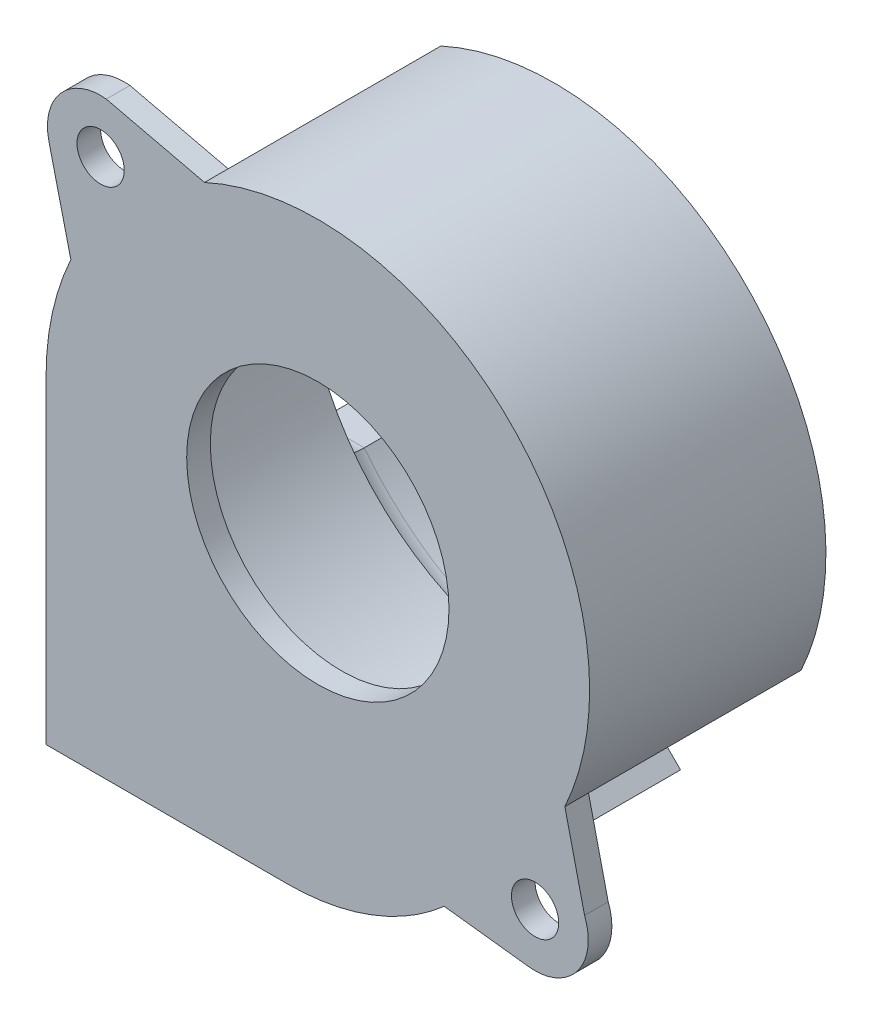
SolidWorks part; units mm, degrees
ref_plane "前视基准面" through (0, 0, 0) normal (0, 0, 1) x (1, 0, 0)
ref_plane "上视基准面" through (0, 0, 0) normal (0, 1, 0) x (1, 0, 0)
ref_plane "右视基准面" through (0, 0, 0) normal (1, 0, 0) x (0, 0, -1)
other "Configuration Table"
sketch "草图1" plane through (0, 0, 0) normal (0, 0, 1) x (1, 0, 0)
  line L4 (-23, 0) -> (-23, -27)
  line L5 (-23, -27) -> (-2.527, -27)
  arc A6 (15.3161, -17.1586) -> (13.0537, -19.5395) centre (28.6345, -32.079) ccw
  arc A7 (15.3161, -17.1586) -> (-23, 0) centre (0, 0) ccw
  arc A8 (-2.527, -27) -> (13.0537, -19.5395) centre (-2.527, -7) ccw
  circle A9 centre (0, 0) radius 11.1
  dimension "D1" = 22.2
extrude "凸台-拉伸1" add sketch "草图1" along normal blind 20
sketch "草图3" plane through (0, 0, 0) normal (0, 0, -1) x (-1, 0, 0)
  circle A0 centre (0, 0) radius 21.1
  dimension "D1" = 42.2
extrude "切除-拉伸11" cut sketch "草图3" against normal blind 18
sketch "草图4" plane through (0, 0, 0) normal (0, 0, -1) x (-1, 0, 0)
  line L0 (23, 0) -> (23, -27) construction
  line L6 (2.527, -27) -> (2.527, -24)
  line L8 (23, -27) -> (23, -24)
  line L15 (23, -27) -> (23, -14.7847)
  line L16 (23, -14.7847) -> (19.0735, -14.7847)
  line L18 (2.527, -27) -> (23, -27)
  arc A1 (2.527, -24) -> (19.0735, -14.7847) centre (0, 0) ccw
  line M8 (2.527, -27) -> (23, -27)
  line M9 (23, -27) -> (23, 0)
  dimension "D1" = 3
extrude "凸台-拉伸2" add sketch "草图4" along normal blind 20 contours A1 L6 L16 M8 M9
fillet "圆角3" radius 3 3 edges at (-2.527, -25.5, 0) (-21.0367, -14.7847, 0) (-11.7421, -21.0834, 0)
sketch "草图5" plane through (0, -27, 0) normal (0, -1, 0) x (1, 0, 0)
  line L0 (-23, 20) -> (-2.527, 20) construction
  line L1 (-23, 20) -> (-23, -20) construction
  line L2 (-2.527, 20) -> (-2.527, -3) construction
  line L3 (-28.9905, 0) -> (25.7032, 0) construction
  line L4 (-2.527, -20) -> (-23, -20) construction
  circle A0 centre (-18, 14) radius 1.5
  circle A1 centre (-6.527, 14) radius 1.5
  circle A2 centre (-6.527, -16) radius 1.5
  circle A3 centre (-18, -16) radius 1.5
  dimension "D1" = 6
  dimension "D3" = 4
  dimension "D2" = 5
  dimension "D4" = 6
  dimension "D5" = 4
  dimension "D6" = 4
extrude "切除-拉伸12" cut sketch "草图5" against normal blind 5
sketch "草图6" plane through (0, 0, 0) normal (0, 0, -1) x (-1, 0, 0)
  line L0 (-18.3848, -18.3848) -> (23.7903, 23.7903) construction
  line L1 (-12.7279, -24.0416) -> (29.4472, 18.1334)
  line L2 (-24.0416, -12.7279) -> (18.1334, 29.4472)
  line L6 (-0.473, -26.7737) -> (-0.473, -21.1274)
  line L7 (17.5417, -11.7847) -> (23, -11.7847)
  line L8 (23, -11.7847) -> (23, 0)
  line L9 (-0.473, -26.7737) -> (-0.473, -21.1274)
  line L10 (17.5417, -11.7847) -> (23, -11.7847)
  line L11 (23, -11.7847) -> (23, 0)
  arc A4 (-13.0537, -19.5395) -> (-0.473, -26.7737) centre (2.527, -7) ccw
  arc A5 (-0.473, -21.1274) -> (17.5417, -11.7847) centre (0, 0) ccw
  arc A6 (23, 0) -> (-15.3161, -17.1586) centre (0, 0) ccw
  arc A7 (-13.0537, -19.5395) -> (-15.3161, -17.1586) centre (-28.6345, -32.079) ccw
  arc A8 (-13.0537, -19.5395) -> (-0.473, -26.7737) centre (2.527, -7) ccw
  arc A9 (-0.473, -21.1274) -> (17.5417, -11.7847) centre (0, 0) ccw
  arc A10 (23, 0) -> (-15.3161, -17.1586) centre (0, 0) ccw
  arc A11 (-13.0537, -19.5395) -> (-15.3161, -17.1586) centre (-28.6345, -32.079) ccw
  circle M9 centre (0, 0) radius 21.1
  arc M10 (-13.0537, -19.5395) -> (-0.473, -26.7737) centre (2.527, -7) ccw
  arc M15 (23, 0) -> (-15.3161, -17.1586) centre (0, 0) ccw
  arc M16 (-15.3161, -17.1586) -> (-13.0537, -19.5395) centre (-28.6345, -32.079) cw
  dimension "D1" = 8
  dimension "D2" = 8
  dimension "D3" = 0
extrude "切除-拉伸13" cut sketch "草图6" against normal blind 18 contours L0 L2 M15 M9 | L0 A10 L1 M16 M10 M9 | L0 L1 M9 M15 | L0 A10 L2 M9
sketch "草图7" plane through (0, 0, 18) normal (0, 0, -1) x (-1, 0, 0)
  line L0 (-20.9048, -9.5911) -> (-22.5726, -16.7378)
  line L1 (-17.8567, -22.8537) -> (-10.6935, -22.0072)
  line L2 (9.5911, 20.9048) -> (17.9032, 22.8589)
  line L3 (22.7609, 17.3361) -> (20.9048, 9.5911)
  line L6 (19.4628, 8.1491) -> (20.9048, 9.5911)
  line L7 (9.5911, 20.9048) -> (8.1491, 19.4628)
  line L8 (-19.4628, -8.1491) -> (-20.9048, -9.5911)
  line L9 (-10.6935, -22.0072) -> (-8.1491, -19.4628)
  arc A1 (-21.5668, -15.2028) -> (-15.2028, -21.5668) centre (-18.3848, -18.3848) ccw construction
  arc A2 (-22.5726, -16.7378) -> (-17.8567, -22.8537) centre (-18.3848, -18.3848) ccw
  circle A3 centre (-18.3848, -18.3848) radius 2
  arc A4 (21.5668, 15.2028) -> (15.2028, 21.5668) centre (18.3848, 18.3848) ccw construction
  arc A5 (22.7609, 17.3361) -> (16.8224, 22.6049) centre (18.3848, 18.3848) ccw
  circle A6 centre (18.3848, 18.3848) radius 2
  arc A9 (-8.1491, -19.4628) -> (19.4628, 8.1491) centre (0, 0) ccw
  arc A10 (20.9048, 9.5911) -> (9.5911, 20.9048) centre (0, 0) ccw
  arc A11 (8.1491, 19.4628) -> (-19.4628, -8.1491) centre (0, 0) ccw
  arc A12 (-20.9048, -9.5911) -> (-15.3161, -17.1586) centre (0, 0) ccw
  arc A13 (-13.0537, -19.5395) -> (-15.3161, -17.1586) centre (-28.6345, -32.079) ccw
  arc A14 (-13.0537, -19.5395) -> (-10.6935, -22.0072) centre (2.527, -7) ccw
  arc A16 (20.9048, 9.5911) -> (9.5911, 20.9048) centre (0, 0) ccw
  arc A18 (-20.9048, -9.5911) -> (-15.3161, -17.1586) centre (0, 0) ccw
  arc A19 (-13.0537, -19.5395) -> (-15.3161, -17.1586) centre (-28.6345, -32.079) ccw
  arc A20 (-13.0537, -19.5395) -> (-10.6935, -22.0072) centre (2.527, -7) ccw
  arc M18 (20.9048, 9.5911) -> (9.5911, 20.9048) centre (0, 0) ccw
  arc M22 (-20.9048, -9.5911) -> (-15.3161, -17.1586) centre (0, 0) ccw
  arc M23 (-15.3161, -17.1586) -> (-13.0537, -19.5395) centre (-28.6345, -32.079) cw
  arc M24 (-13.0537, -19.5395) -> (-10.6935, -22.0072) centre (2.527, -7) ccw
  dimension "D1" = 0
extrude "凸台-拉伸3" add sketch "草图7" against normal blind 2 contours L0 A2 L1 A3 M24 M23 M22 | L3 A5 L2 A6 M18
sketch "草图8" plane through (0, 0, -20) normal (0, 0, -1) x (-1, 0, 0)
  line L4 (2.527, -24) -> (2.527, -27)
  line L5 (2.527, -27) -> (23, -27)
  line L6 (23, -27) -> (23, -14.7847)
  line L7 (23, -14.7847) -> (19.0735, -14.7847)
  line L8 (2.527, -24) -> (2.527, -27)
  line L9 (2.527, -27) -> (23, -27)
  line L10 (23, -27) -> (23, -14.7847)
  line L11 (23, -14.7847) -> (19.0735, -14.7847)
  arc A1 (2.527, -24) -> (19.0735, -14.7847) centre (0, 0) ccw
  arc A2 (2.527, -24) -> (19.0735, -14.7847) centre (0, 0) ccw
  dimension "D1" = 0
extrude "凸台-拉伸4" add sketch "草图8" along normal blind 2
